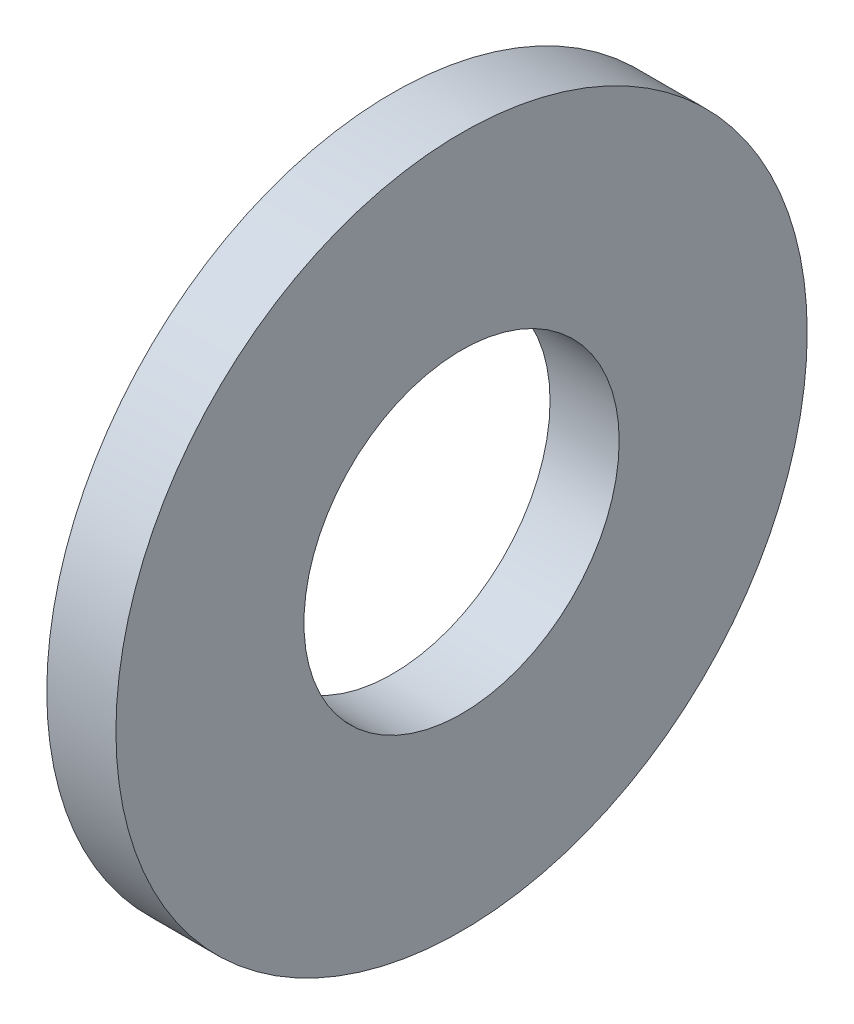
SolidWorks part; units mm, degrees
material "Wrought Stainless Steel"
ref_plane "Front Plane" through (0, 0, 0) normal (0, 0, 1) x (1, 0, 0)
ref_plane "Top Plane" through (0, 0, 0) normal (0, 1, 0) x (1, 0, 0)
ref_plane "Right Plane" through (0, 0, 0) normal (1, 0, 0) x (0, 0, -1)
sketch "Sketch1" plane through (0, 0, 0) normal (1, 0, 0) x (0, 0, -1)
  circle A0 centre (0, 0) radius 6.35
  circle A1 centre (0, 0) radius 2.8956
  dimension "OD" = 12.7
  dimension "ID" = 5.7912
extrude "Boss-Extrude1" add sketch "Sketch1" along normal blind 1.27
